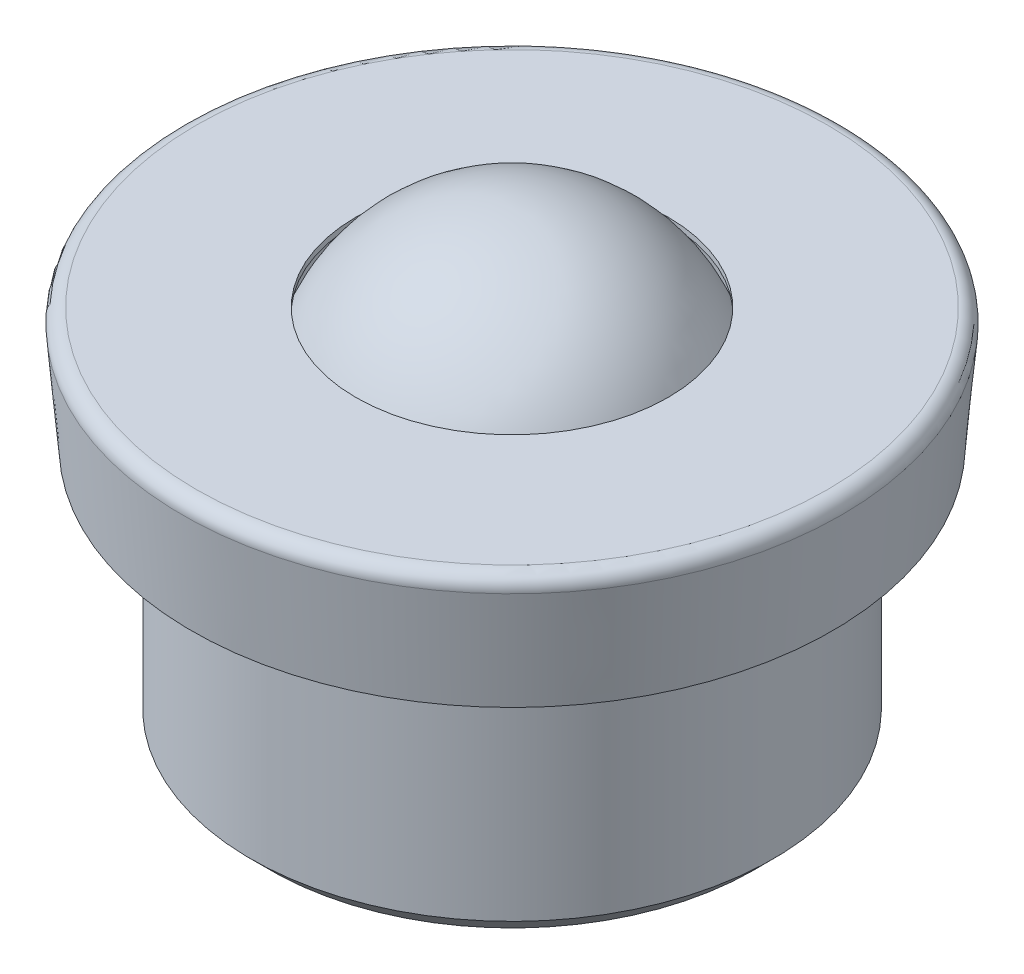
SolidWorks part; units mm, degrees
ref_plane "Front Plane" through (0, 0, 0) normal (0, 0, 1) x (1, 0, 0)
ref_plane "Top Plane" through (0, 0, 0) normal (0, 1, 0) x (1, 0, 0)
ref_plane "Right Plane" through (0, 0, 0) normal (1, 0, 0) x (0, 0, -1)
sketch "Sketch1" plane through (0, 0, 0) normal (0, 0, 1) x (1, 0, 0)
  line L2 (7.1183, 4.0125) -> (15.0812, 4.0125)
  line L12 (11.9062, -1.5875) -> (11.9063, -12.7)
  line L13 (11.9063, -12.7) -> (-11.9062, -12.7)
  line L14 (0, 0) -> (0, -12.7) construction
  line L15 (-11.9062, -1.5875) -> (-11.9062, -12.7)
  line L16 (7.1183, 3.7585) -> (14.8041, 3.7585)
  line L30 (11.9062, -1.5875) -> (14.1046, -1.5875)
  line L32 (14.1046, -1.5875) -> (14.3586, -1.3335)
  line L37 (7.1183, 4.0125) -> (7.1183, 3.7585)
  line L41 (14.6024, -1.4605) -> (14.3475, -1.4605)
  line L42 (14.3475, -1.4605) -> (14.3586, -1.3335)
  line L43 (14.8041, 3.7585) -> (14.3586, -1.3335)
  line L44 (14.6024, -1.4605) -> (15.0812, 4.0125)
  line L45 (-14.6024, -1.4605) -> (-15.0812, 4.0125)
  line L46 (-14.8041, 3.7585) -> (-14.3586, -1.3335)
  line L47 (-14.3475, -1.4605) -> (-14.3586, -1.3335)
  line L48 (-14.6024, -1.4605) -> (-14.3475, -1.4605)
  line L49 (-7.1183, 4.0125) -> (-7.1183, 3.7585)
  line L50 (-14.1046, -1.5875) -> (-14.3586, -1.3335)
  line L51 (-11.9062, -1.5875) -> (-14.1046, -1.5875)
  line L52 (-7.1183, 3.7585) -> (-14.8041, 3.7585)
  line L53 (-7.1183, 4.0125) -> (-15.0812, 4.0125)
  circle A0 centre (0, 0) radius 7.9375
  arc A15 (-9.7802, 3.7585) -> (9.7802, 3.7585) centre (0, 0) ccw
  arc A25 (8.2823, 4.4848) -> (7.1183, 4.0125) centre (7.1183, 5.6831) ccw construction
  arc A26 (7.1565, 4.8092) -> (8.2823, 4.4848) centre (7.1789, 2.7713) cw construction
  arc A27 (7.1593, 4.5552) -> (8.2969, 4.1616) centre (7.1789, 2.7713) cw construction
  arc A28 (8.2969, 4.1616) -> (7.1183, 3.7585) centre (7.1183, 5.6831) ccw construction
  arc A29 (15.0812, 4.0125) -> (13.2752, 2.3683) centre (13.4303, 4.012) cw construction
  arc A30 (14.8041, 3.7585) -> (13.299, 2.6212) centre (13.4303, 4.012) cw construction
  point P19 (6.9913, 3.7585)
  point P31 (14.3475, -1.4605)
  point P32 (-6.9913, 3.7585)
  point P40 (-7.9375, 0)
  point P41 (7.9375, 0)
  point P65 (0, 7.9375)
  dimension "D1" = 0.254
  dimension "D3" = 85
  dimension "D5" = 0.254
  dimension "Ball Diameter" = 15.875
  dimension "D4" = 0.254
  dimension "D8" = 5.6
  dimension "D6" = 2.54
  dimension "D7" = 0.127
  dimension "Diameter" = 23.8125
  dimension "Depth" = 20.6375
  dimension "Height" = 9.525
  dimension "D10" = 0.254
  dimension "Flange Diameter" = 30.1625
  dimension "D2" = 0.127
sketch "Sketch2" plane through (0, 0, 0) normal (0, 0, 1) x (1, 0, 0)
  line L1 (0, -7.9375) -> (0, 7.9375)
  circle A0 centre (0, 0) radius 7.9375 construction
  arc A1 (0, -7.9375) -> (0, 7.9375) centre (0, 0) ccw
revolve "Revolve1" add sketch "Sketch2" angle 360 about L1
sketch "Sketch3" plane through (0, 0, 0) normal (0, 0, 1) x (1, 0, 0)
  line L8 (14.8041, 3.7585) -> (14.3586, -1.3335) construction
  line L9 (7.1183, 3.7585) -> (14.8041, 3.7585) construction
  line L10 (7.1183, 4.0125) -> (7.1183, 3.7585) construction
  line L11 (7.1183, 4.0125) -> (15.0812, 4.0125) construction
  line L12 (14.6024, -1.4605) -> (15.0812, 4.0125) construction
  line L13 (14.6024, -1.4605) -> (14.3475, -1.4605) construction
  line L14 (14.3475, -1.4605) -> (14.3586, -1.3335) construction
  line L15 (14.8041, 3.7585) -> (14.3586, -1.3335)
  line L16 (7.1183, 3.7585) -> (14.8041, 3.7585)
  line L17 (7.1183, 4.0125) -> (7.1183, 3.7585)
  line L18 (7.1183, 4.0125) -> (15.0812, 4.0125)
  line L19 (14.6024, -1.4605) -> (15.0812, 4.0125)
  line L20 (14.6024, -1.4605) -> (14.3475, -1.4605)
  line L21 (14.3475, -1.4605) -> (14.3586, -1.3335)
revolve "Revolve2" add sketch "Sketch3" angle 360 about L14
sketch "Sketch4" plane through (0, 0, 0) normal (0, 0, 1) x (1, 0, 0)
  line L0 (14.8041, 3.7585) -> (14.3586, -1.3335) construction
  line L1 (11.9062, -1.5875) -> (14.1046, -1.5875) construction
  line L3 (11.9063, -12.7) -> (-11.9062, -12.7) construction
  line L4 (11.9062, -1.5875) -> (11.9063, -12.7) construction
  line L6 (7.1183, 3.7585) -> (14.8041, 3.7585) construction
  line L7 (14.1046, -1.5875) -> (14.3586, -1.3335) construction
  line L8 (11.9062, -1.5875) -> (14.1046, -1.5875)
  line L14 (11.9063, -12.7) -> (0, -12.7)
  line L15 (11.9062, -1.5875) -> (11.9063, -12.7)
  line L18 (0, -12.7) -> (0, -10.4775)
  line L19 (0, 0) -> (0, -12.7) construction
  line L21 (9.7802, 3.7585) -> (14.8041, 3.7585)
  line L22 (14.8041, 3.7585) -> (14.3586, -1.3335)
  line L23 (14.1046, -1.5875) -> (14.3586, -1.3335)
  arc A1 (-9.7802, 3.7585) -> (9.7802, 3.7585) centre (0, 0) ccw construction
  arc A5 (0, -10.4775) -> (9.7802, 3.7585) centre (0, 0) ccw
revolve "Revolve3" add sketch "Sketch4" angle 360 about L14
sketch "Sketch6" plane through (0, -12.7, 0) normal (0, -1, 0) x (1, 0, 0)
  circle A0 centre (0, 0) radius 0.635
  dimension "D1" = 1.27
extrude "Cut-Extrude1" cut sketch "Sketch6" against normal through all
chamfer "Chamfer1" distance 0.889 angle 45 1 edges at (-11.9062, -12.7, 0)
fillet "Fillet1" radius 0.635 1 edges at (-15.0812, 4.0125, 0)
sketch "Sketch5" plane through (0, 0, 0) normal (0, 0, 1) x (1, 0, 0)
  line L0 (7.1183, 4.0125) -> (-7.1183, 4.0125) construction
  line L2 (15.0812, 4.0125) -> (-15.0812, 4.0125) construction
  circle A0 centre (0, 0) radius 7.9375 construction
  arc A1 (-6.8486, 4.0125) -> (6.8486, 4.0125) centre (0, 0) ccw
